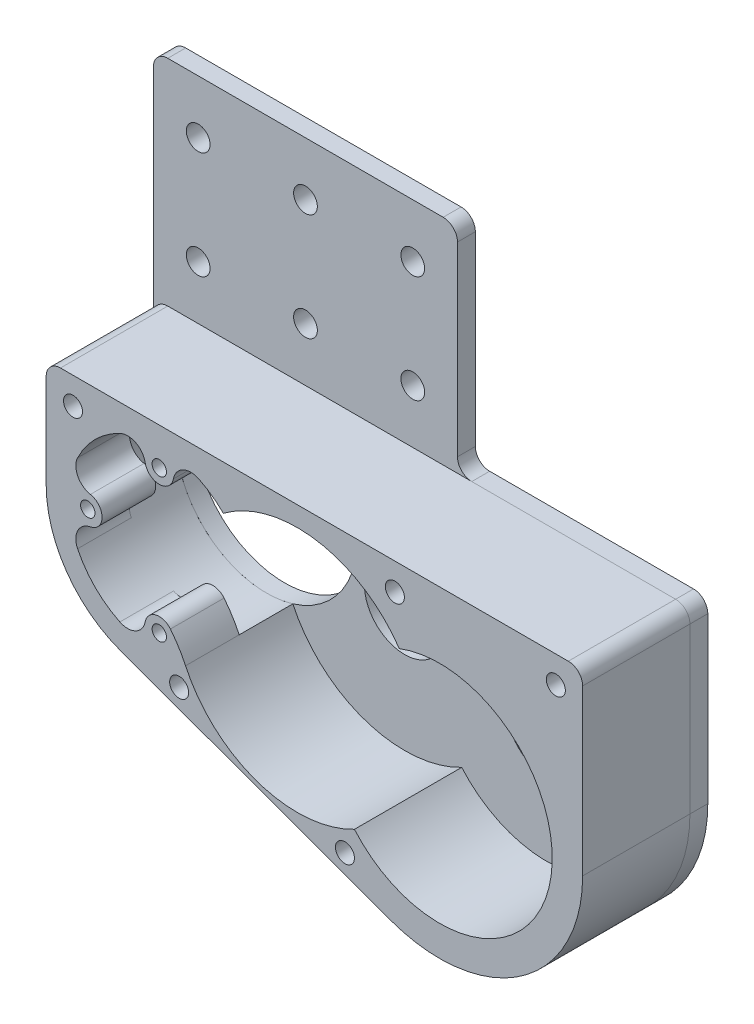
SolidWorks part; units mm, degrees
ref_plane "Front Plane" through (0, 0, 0) normal (0, 0, 1) x (1, 0, 0)
ref_plane "Top Plane" through (0, 0, 0) normal (0, 1, 0) x (1, 0, 0)
ref_plane "Right Plane" through (0, 0, 0) normal (1, 0, 0) x (0, 0, -1)
sketch "Gear&Motor Layout" plane through (0, 0, 0) normal (0, 0, 1) x (1, 0, 0)
  line L1 (-139.7, 63.5) -> (50.8, 63.5) construction
  line L2 (-99.5384, 24.9428) -> (0, 0) construction
  circle A1 centre (-99.5384, 24.9428) radius 32.2072 construction
  circle A2 centre (0, 0) radius 14.2875 construction
  circle A3 centre (-99.5384, 24.9428) radius 25.4 construction
  circle A4 centre (-124.9384, 24.9428) radius 2.5527 construction
  circle A5 centre (-99.5384, 50.3428) radius 2.5527 construction
  circle A6 centre (-74.1384, 24.9428) radius 2.5527 construction
  circle A7 centre (-99.5384, -0.4572) radius 2.5527 construction
  circle A11 centre (-50.5084, 12.6566) radius 41.91 construction
  circle A12 centre (-50.5084, 12.6566) radius 43.18 construction
  circle A15 centre (0, 0) radius 38.1 construction
  circle A16 centre (0, 0) radius 39.37 construction
  circle A17 centre (-50.5084, 12.6566) radius 13.97 construction
  circle A18 centre (-50.5084, 12.6566) radius 15.24 construction
  circle A19 centre (-99.5384, 24.9428) radius 8.636 construction
  circle A20 centre (-99.5384, 24.9428) radius 8.89 construction
  point P5 (-124.9384, 24.9428)
  point P8 (-99.5384, 50.3428)
  point P10 (-74.1384, 24.9428)
  point P14 (-99.5384, -0.4572)
  dimension "D4" = 83.82
  dimension "D1" = 28.575
  dimension "D2" = 64.4144
  dimension "D3" = 50.8
  dimension "D5" = 17.272
  dimension "D6" = 17.78
  dimension "D7" = 86.36
  dimension "D8" = 27.94
  dimension "D9" = 30.48
  dimension "D10" = 76.2
  dimension "D11" = 78.74
  dimension "D13" = 63.5
  dimension "D14" = 5.1054
  dimension "D16" = 6.35
  dimension "D12" = 50.8
  dimension "D15" = 190.5
sketch "Sketch2" plane through (0, 0, 0) normal (0, 0, 1) x (1, 0, 0)
  line L0 (50.8, 63.5) -> (-139.7, 63.5)
  line L1 (50.8, 63.5) -> (50.8, 0)
  line L2 (-17.39, -47.7308) -> (-113.2866, -12.7923)
  line L3 (-139.7, 24.9428) -> (-139.7, 63.5)
  arc A0 (50.8, 0) -> (-17.39, -47.7308) centre (0, 0) cw
  arc A1 (-113.2866, -12.7923) -> (-139.7, 24.9428) centre (-99.5384, 24.9428) cw
extrude "Boss-Extrude1" add sketch "Sketch2" against normal blind 6.35
sketch "Sketch3" plane through (0, 0, 0) normal (0, 0, 1) x (1, 0, 0)
  line L0 (-139.7, 63.5) -> (-139.7, 139.7)
  line L1 (-139.7, 139.7) -> (-31.75, 139.7)
  line L2 (-31.75, 139.7) -> (-31.75, 63.5)
  line L5 (50.8, 0) -> (50.8, 63.5) construction
  line L6 (50.8, 63.5) -> (-139.7, 63.5) construction
  line L7 (-31.75, 63.5) -> (-139.7, 63.5)
  dimension "D1" = 82.55
  dimension "D2" = 76.2
extrude "Boss-Extrude2" add sketch "Sketch3" against normal up to surface (6.35 mm away) up to face at (-50.333, 11.5841, -6.35)
fillet "Fillet1" radius 5.08 4 edges at (50.8, 63.5, -3.175) (-31.75, 63.5, -3.175) (-31.75, 139.7, -3.175) (-139.7, 139.7, -3.175)
sketch "Sketch4" plane through (0, 0, 0) normal (0, 0, 1) x (1, 0, 0)
  circle A0 centre (0, 0) radius 14.2875 construction
  circle A1 centre (0, 0) radius 14.2875
  circle A2 centre (-50.5084, 12.6566) radius 14.2875
  circle A3 centre (-99.5384, 24.9428) radius 32.2024
  dimension "D1" = 64.4049
extrude "Cut-Extrude1" cut sketch "Sketch4" against normal up to next
hole_wizard "Tap Drill for 1/4-20 Tap1" positions "Sketch10" profile "Sketch9" hole size "1/4-20" standard "ANSI Inch" end condition through all
sketch "Sketch10" plane through (0, 0, 0) normal (0, 0, 1) x (1, 0, 0)
  line L0 (50.8, 0) -> (50.8, 58.42) construction
  line L1 (-139.7, 63.5) -> (50.8, 63.5) construction
  line L2 (-92.4826, -13.6136) -> (-33.6126, -35.062) construction
  line L4 (-113.2866, -12.7923) -> (-17.39, -47.7308) construction
  line L5 (-33.6126, -35.062) -> (-30.0888, -25.3901) construction
  line L6 (-89.5962, -5.6914) -> (-92.4826, -13.6136) construction
  line L7 (-139.7, 134.62) -> (-139.7, 24.9428) construction
  circle A0 centre (-50.5084, 12.6566) radius 43.18 construction
  circle A1 centre (0, 0) radius 39.37 construction
  circle A2 centre (-99.5384, 24.9428) radius 32.2072 construction
  point P0 (-33.6126, -35.062)
  point P2 (-92.4826, -13.6136)
  point P4 (-130.175, 53.975)
  point P6 (-15.875, 53.975)
  point P8 (41.275, 53.975)
  dimension "D1" = 9.525
  dimension "D2" = 9.525
  dimension "D3" = 6.35
  dimension "2" = 57.15
  dimension "D4" = 9.525
  dimension "D5" = 9.525
sketch "Sketch9" plane through (-33.6126, -35.062, 0) normal (1, 0, 0) x (0, -1, 0)
  line L0 (0, 0) -> (0, 6.35)
  line L1 (0, 6.35) -> (2.5527, 6.35)
  line L2 (2.5527, 6.35) -> (2.5527, 0)
  line L5 (2.5527, 0) -> (0, 0)
  line L11 (0, -6.35) -> (0, 107.95) construction
  dimension "Thru Hole Dia." = 5.1054
  dimension "Thru Hole Depth" = 6.35
hole_wizard "5/16 Clearance Hole1" positions "Sketch14" profile "Sketch12" hole size "5/16" standard "ANSI Inch" end condition through all
sketch "Sketch14" plane through (0, 0, 0) normal (0, 0, 1) x (1, 0, 0)
  line L0 (-139.7, 134.62) -> (-139.7, 24.9428) construction
  line L1 (-31.75, 68.58) -> (-31.75, 134.62) construction
  line L2 (-123.825, 82.55) -> (-85.725, 82.55) construction
  line L4 (-47.625, 82.55) -> (-85.725, 82.55) construction
  line L6 (-47.625, 120.65) -> (-47.625, 82.55) construction
  line L8 (-36.83, 139.7) -> (-134.62, 139.7) construction
  point P0 (-123.825, 120.65)
  point P2 (-85.725, 120.65)
  point P4 (-47.625, 120.65)
  point P6 (-47.625, 82.55)
  point P8 (-85.725, 82.55)
  point P10 (-123.825, 82.55)
  point P35 (-47.625, 101.6)
  dimension "D1" = 15.875
  dimension "D2" = 15.875
  dimension "D3" = 38.1
  dimension "D4" = 38.1
sketch "Sketch12" plane through (-123.825, 120.65, 0) normal (1, 0, 0) x (0, -1, 0)
  line L0 (0, 0) -> (0, 6.35)
  line L1 (0, 6.35) -> (4.2164, 6.35)
  line L2 (4.2164, 6.35) -> (4.2164, 0)
  line L5 (4.2164, 0) -> (0, 0)
  line L11 (0, -6.35) -> (0, 107.95) construction
  dimension "Thru Hole Dia." = 8.4328
  dimension "Thru Hole Depth" = 6.35
sketch "Sketch15" plane through (0, 0, 0) normal (0, 0, 1) x (1, 0, 0)
  line L0 (-113.2866, -12.7923) -> (-17.39, -47.7308) construction
  line L1 (50.8, 0) -> (50.8, 58.42) construction
  line L3 (-113.2866, -12.7923) -> (-17.39, -47.7308)
  line L4 (50.8, 0) -> (50.8, 58.42)
  line L6 (-139.7, 24.9428) -> (-139.7, 58.42)
  line L7 (-134.62, 63.5) -> (45.72, 63.5)
  arc A0 (-139.7, 24.9428) -> (-113.2866, -12.7923) centre (-99.5384, 24.9428) ccw construction
  arc A1 (-17.39, -47.7308) -> (50.8, 0) centre (0, 0) ccw construction
  arc A2 (50.8, 58.42) -> (45.72, 63.5) centre (45.72, 58.42) ccw construction
  arc A3 (-139.7, 24.9428) -> (-113.2866, -12.7923) centre (-99.5384, 24.9428) ccw
  arc A4 (-17.39, -47.7308) -> (50.8, 0) centre (0, 0) ccw
  arc A5 (50.8, 58.42) -> (45.72, 63.5) centre (45.72, 58.42) ccw
  arc A6 (-139.7, 58.42) -> (-134.62, 63.5) centre (-134.62, 58.42) cw
  circle A7 centre (-99.5384, 24.9428) radius 32.2024 construction
  arc A8 (-76.7778, 47.7233) -> (-90.2097, -5.8788) centre (-99.5384, 24.9428) ccw
  arc A9 (-90.2097, -5.8788) -> (-30.2412, -26.1892) centre (-50.5084, 12.6566) ccw
  arc A10 (-30.2412, -26.1892) -> (-14.318, 37.355) centre (0, 0) ccw
  arc A11 (-14.318, 37.355) -> (-76.7778, 47.7233) centre (-50.5084, 12.6566) ccw
  dimension "D1" = 87.63
  dimension "D2" = 80.01
extrude "Boss-Extrude3" add sketch "Sketch15" along normal blind 38.1 separate body
sketch "Sketch16" plane through (0, 0, 38.1) normal (0, 0, 1) x (1, 0, 0)
  circle A0 centre (-15.875, 53.975) radius 3.3782 construction
  circle A1 centre (-15.875, 53.975) radius 3.3782
  circle A2 centre (-92.4826, -13.6136) radius 3.3782 construction
  circle A3 centre (-33.6126, -35.062) radius 3.3782 construction
  circle A12 centre (41.275, 53.975) radius 3.3782 construction
  circle A13 centre (-130.175, 53.975) radius 3.3782 construction
  circle A14 centre (-92.4826, -13.6136) radius 3.3782
  circle A15 centre (-33.6126, -35.062) radius 3.3782
  circle A16 centre (41.275, 53.975) radius 3.3782
  circle A17 centre (-130.175, 53.975) radius 3.3782
extrude "Cut-Extrude3" cut sketch "Sketch16" against normal through all both and the other way through all
sketch "Sketch17" plane through (0, 0, 38.1) normal (0, 0, 1) x (1, 0, 0)
  circle A0 centre (-99.5384, 50.3428) radius 2.5527
  circle A1 centre (-99.5384, -0.4572) radius 2.5527
  circle A2 centre (-99.5384, 24.9428) radius 32.2024 construction
  arc A3 (-95.5861, 2.7342) -> (-104.5307, 0.4829) centre (-99.5384, -0.4572) ccw
  arc A4 (-90.2097, -5.8788) -> (-30.2412, -26.1892) centre (-50.5084, 12.6566) ccw construction
  arc A5 (-90.2097, -5.8788) -> (-95.5861, 2.7342) centre (-128.2437, -23.6358) ccw
  arc A6 (-104.5307, 0.4829) -> (-113.53, -4.0612) centre (-110.771, 1.6581) cw
  arc A7 (-76.7778, 47.7233) -> (-90.2097, -5.8788) centre (-99.5384, 24.9428) ccw construction
  arc A8 (-113.53, -4.0612) -> (-90.2097, -5.8788) centre (-99.5384, 24.9428) ccw
  arc A9 (-104.5307, 49.4027) -> (-94.5462, 49.4027) centre (-99.5384, 50.3428) ccw
  arc A10 (-94.5462, 49.4027) -> (-85.5469, 53.9468) centre (-88.3059, 48.2275) cw
  arc A11 (-104.5307, 49.4027) -> (-113.53, 53.9468) centre (-110.771, 48.2275) ccw
  arc A12 (-113.53, 53.9468) -> (-85.5469, 53.9468) centre (-99.5384, 24.9428) cw
  arc A13 (-123.9983, 19.9505) -> (-128.5425, 10.9512) centre (-122.8232, 13.7102) ccw
  arc A14 (-128.5425, 10.9512) -> (-128.5425, 38.9344) centre (-99.5384, 24.9428) cw
  arc A15 (-123.9983, 29.9351) -> (-128.5425, 38.9344) centre (-122.8232, 36.1754) cw
  arc A16 (-123.9983, 19.9505) -> (-123.9983, 29.9351) centre (-124.9384, 24.9428) ccw
  circle A17 centre (-124.9384, 24.9428) radius 2.5527
  point P36 (-99.5384, 24.9428)
  dimension "D1" = 5.1054
  dimension "D2" = 5.08
  dimension "D3" = 6.35
  dimension "D4" = 6.35
  dimension "D5" = 6.35
  dimension "D6" = 5.08
  dimension "D7" = 2
extrude "Boss-Extrude4" add sketch "Sketch17" against normal up to surface (19.05 mm away)
sketch "Sketch18" plane through (0, 0, -6.35) normal (0, 0, -1) x (-1, 0, 0)
  circle A0 centre (-41.275, 53.975) radius 3.3782
  circle A1 centre (15.875, 53.975) radius 3.3782
  circle A2 centre (33.6126, -35.062) radius 3.3782
  circle A3 centre (92.4826, -13.6136) radius 3.3782
  circle A4 centre (130.175, 53.975) radius 3.3782
  dimension "D1" = 6.7564
extrude "Cut-Extrude4" cut sketch "Sketch18" against normal through all both and the other way through all
